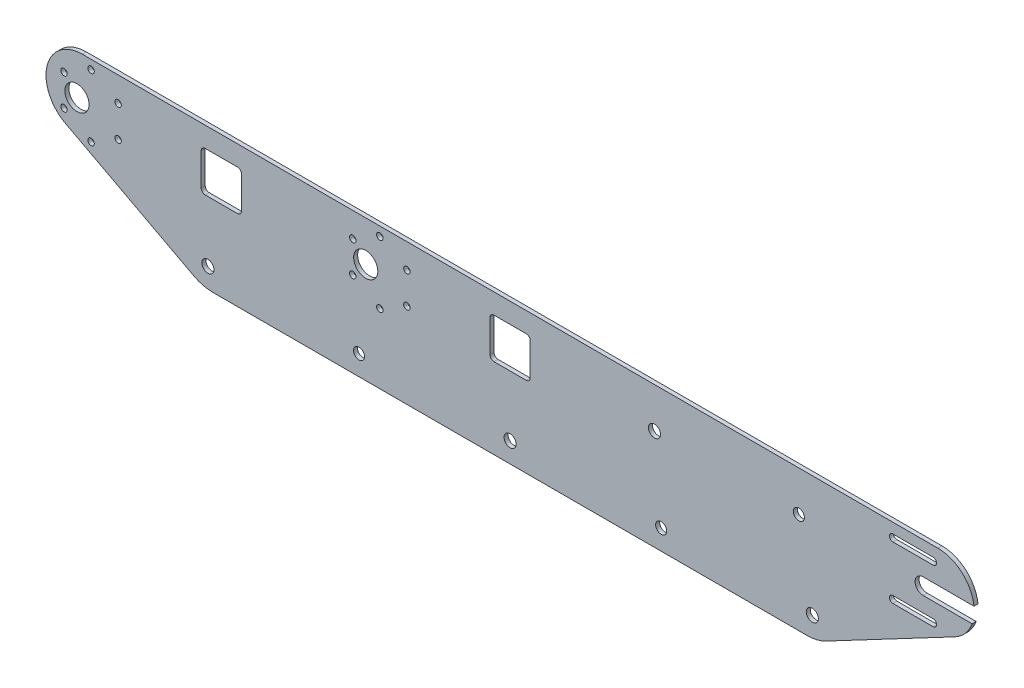
SolidWorks part; units mm, degrees
ref_plane "Plan de face" through (0, 0, 0) normal (0, 0, 1) x (1, 0, 0)
ref_plane "Plan de dessus" through (0, 0, 0) normal (0, 1, 0) x (1, 0, 0)
ref_plane "Plan de droite" through (0, 0, 0) normal (1, 0, 0) x (0, 0, -1)
sketch "Esquisse1" plane through (0, 0, 0) normal (0, 0, 1) x (1, 0, 0)
  line L0 (0, 0) -> (0, 122.747) construction
  line L1 (-215, -20) -> (215, -20) construction
  line L2 (-215, -20) -> (-215, 20) construction
  line L3 (-215, 20) -> (215, 20) construction
  line L4 (215, -20) -> (215, 20) construction
  line L5 (-215, -20) -> (215, 20) construction
  line L6 (-215, 20) -> (215, -20) construction
  line L7 (-1220, 0) -> (-150, 0) construction
  line L8 (-284.959, 40) -> (-247.3, 40)
  line L9 (248.3333, 40) -> (284.959, 40)
  line L10 (150, 0) -> (150, -20) construction
  line L11 (150, -20) -> (-150, -20) construction
  line L12 (-150, 0) -> (-150, -20) construction
  line L13 (150, 0) -> (-150, -20) construction
  line L14 (150, -20) -> (-150, 0) construction
  line L15 (-284.959, 40) -> (-247.3, 20.1016)
  line L16 (-152.4795, -30) -> (152.4795, -30)
  line L17 (284.959, 40) -> (248.3333, 20.6476)
  line L18 (-215, 20) -> (-71.6667, 20) construction
  line L19 (-71.6667, 20) -> (71.6667, 20) construction
  line L20 (71.6667, 20) -> (215, 20) construction
  line L21 (150, 0) -> (193.5165, 0) construction
  line L27 (-247.3, 20.1016) -> (-152.4795, -30)
  line L28 (248.3333, 20.6476) -> (152.4795, -30)
  line L29 (-247.3, 40) -> (248.3333, 40)
  circle A0 centre (-215, 20) radius 6
  circle A1 centre (-150, -20) radius 3
  circle A2 centre (150, -20) radius 3
  circle A3 centre (215, 20) radius 3
  circle A4 centre (0, -20) radius 3
  circle A5 centre (-71.6667, 20) radius 6
  circle A6 centre (71.6667, 20) radius 3
  point P0 (0, 0)
  point P8 (0, -10)
  point P21 (0, -30)
  dimension "D8" = 6
  dimension "D11" = 12
  dimension "D1" = 430
  dimension "D2" = 40
  dimension "D3" = 300
  dimension "D4" = 20
  dimension "D5" = 15
  dimension "D6" = 10
  dimension "D7" = 10
extrude "Boss.-Extru.1" add sketch "Esquisse1" along normal blind 2
fillet "Congé1" radius 18 2 edges at (-284.959, 40, 1) (284.959, 40, 1)
fillet "Congé2" radius 20 2 edges at (-152.4795, -30, 1) (152.4795, -30, 1)
hole_wizard "Dégagement M32" positions "Esquisse6" profile "Esquisse5" hole size "M3" standard "Ansi Metric" end condition through all
sketch "Esquisse6" plane through (0, 0, 0) normal (0, 0, -1) x (-1, 0, 0)
  line L0 (-200, 33.2288) -> (-200, 6.7712)
  circle A0 centre (-215, 20) radius 20
  circle A1 centre (-215, 20) radius 7.5
  point P0 (-200, 33.2288)
  point P2 (-200, 6.7712)
  dimension "D1" = 40
  dimension "D2" = 15
  dimension "D3" = 15
sketch "Esquisse5" plane through (200, 33.2288, 0) normal (1, 0, 0) x (0, 1, 0)
  line L0 (0, 0) -> (0, 2)
  line L1 (0, 2) -> (1.7, 2)
  line L2 (1.7, 2) -> (1.7, 0)
  line L5 (1.7, 0) -> (0, 0)
  line L11 (0, -6.35) -> (0, 107.95) construction
  dimension "Diamètre du perçage jusqu'au prochain" = 3.4
  dimension "Profondeur du perçage jusqu'au prochain" = 2
sketch "Esquisse4" plane through (0, 0, 0) normal (0, 0, -1) x (-1, 0, 0)
  line L0 (-215, 24) -> (-246.6987, 24)
  line L1 (-215, 24) -> (-205, 24)
  line L2 (-215, 16) -> (-239.4934, 16)
  line L3 (-215, 16) -> (-205, 16)
  line L4 (-215, 24) -> (-215, 16)
  line L8 (-147.5205, -30) -> (147.5205, -30)
  line L9 (156.8641, -27.6833) -> (220.7728, 6.0851)
  line L10 (156.8641, -27.6833) -> (220.7728, 6.0851)
  line L11 (212.3636, 40) -> (-212.3636, 40)
  line L12 (212.3636, 40) -> (-212.3636, 40)
  line L13 (-220.7728, 6.0851) -> (-156.8641, -27.6833)
  line L14 (-220.7728, 6.0851) -> (-156.8641, -27.6833)
  line L16 (-147.5205, -30) -> (147.5205, -30)
  arc A2 (-205, 24) -> (-205, 16) centre (-205, 20) cw
  circle A3 centre (-215, 20) radius 3 construction
  arc A6 (147.5205, -30) -> (156.8641, -27.6833) centre (147.5205, -10) ccw
  arc A7 (147.5205, -30) -> (156.8641, -27.6833) centre (147.5205, -10) ccw
  arc A8 (-156.8641, -27.6833) -> (-147.5205, -30) centre (-147.5205, -10) ccw
  arc A9 (-156.8641, -27.6833) -> (-147.5205, -30) centre (-147.5205, -10) ccw
  arc A12 (220.7728, 6.0851) -> (212.3636, 40) centre (212.3636, 22) ccw
  arc A13 (220.7728, 6.0851) -> (212.3636, 40) centre (212.3636, 22) ccw
  arc A14 (-212.3636, 40) -> (-220.7728, 6.0851) centre (-212.3636, 22) ccw
  arc A15 (-212.3636, 40) -> (-220.7728, 6.0851) centre (-212.3636, 22) ccw
  point P12 (-215, 20)
  circle M25 centre (-215, 20) radius 3
  arc M41 (-212.3636, 40) -> (-220.7728, 6.0851) centre (-212.3636, 22) ccw
  dimension "D2" = 10
  dimension "D3" = 8
  dimension "D1" = 0
extrude "Enlèv. mat.-Extru.1" cut sketch "Esquisse4" against normal through all contours A2 L1 L3 M25 | L2 L0 M25 M41
sketch "Esquisse7" plane through (0, 0, 0) normal (0, 0, -1) x (-1, 0, 0)
  line L0 (-200, 34.9288) -> (-210, 34.9288)
  line L1 (-200, 8.4712) -> (-210, 8.4712)
  line L2 (-210, 31.5288) -> (-200, 31.5288)
  line L3 (-200, 31.5288) -> (-190, 31.5288)
  line L4 (-210, 5.0712) -> (-200, 5.0712)
  line L5 (-190, 34.9288) -> (-200, 34.9288)
  line L6 (-200, 31.5288) -> (-200, 34.9288)
  line L7 (-200, 5.0712) -> (-190, 5.0712)
  line L8 (-190, 8.4712) -> (-200, 8.4712)
  line L9 (-200, 5.0712) -> (-200, 8.4712)
  circle A0 centre (-200, 33.2288) radius 1.7 construction
  arc A1 (-190, 34.9288) -> (-190, 31.5288) centre (-190, 33.2288) cw
  arc A2 (-210, 34.9288) -> (-210, 31.5288) centre (-210, 33.2288) ccw
  arc A3 (-190, 8.4712) -> (-190, 5.0712) centre (-190, 6.7712) cw
  arc A4 (-210, 8.4712) -> (-210, 5.0712) centre (-210, 6.7712) ccw
  circle A5 centre (-200, 6.7712) radius 1.7 construction
  point P11 (-200, 33.2288)
  point P19 (-200, 6.7712)
  circle M8 centre (-200, 33.2288) radius 1.7
  circle M9 centre (-200, 6.7712) radius 1.7
  dimension "D1" = 10
extrude "Enlèv. mat.-Extru.2" cut sketch "Esquisse7" against normal through all contours L1 A4 L4 M9 | A3 L8 L7 M9 | A1 L5 L3 M8 | L0 A2 L2 M8
sketch "Esquisse8" plane through (0, 0, 0) normal (0, 0, -1) x (-1, 0, 0)
  line L0 (199.334, 20) -> (153.1405, 20) construction
  line L1 (51.2433, 27.75) -> (51.2433, 12.25) construction
  line L2 (194.5766, 27.75) -> (194.5766, 12.25) construction
  line L3 (194.5766, 12.25) -> (208, 4.5) construction
  line L4 (208, 4.5) -> (221.4234, 12.25) construction
  line L5 (221.4234, 12.25) -> (221.4234, 27.75) construction
  line L6 (221.4234, 27.75) -> (208, 35.5) construction
  line L7 (208, 35.5) -> (194.5766, 27.75) construction
  line L8 (51.2433, 12.25) -> (64.6667, 4.5) construction
  line L9 (64.6667, 4.5) -> (78.0901, 12.25) construction
  line L10 (78.0901, 12.25) -> (78.0901, 27.75) construction
  line L11 (-220.7728, 6.0851) -> (-156.8641, -27.6833)
  line L12 (-220.7728, 6.0851) -> (-156.8641, -27.6833)
  line L13 (-147.5205, -30) -> (147.5205, -30)
  line L14 (156.8641, -27.6833) -> (220.7728, 6.0851)
  line L15 (156.8641, -27.6833) -> (220.7728, 6.0851)
  line L16 (212.3636, 40) -> (-212.3636, 40)
  line L17 (212.3636, 40) -> (-212.3636, 40)
  line L23 (-147.5205, -30) -> (147.5205, -30)
  line L25 (-205, 16) -> (-229.3341, 16)
  line L26 (-205, 16) -> (-229.3341, 16)
  line L27 (-230.2521, 24) -> (-205, 24)
  line L28 (-230.2521, 24) -> (-205, 24)
  line L31 (78.0901, 27.75) -> (64.6667, 35.5) construction
  line L32 (64.6667, 35.5) -> (51.2433, 27.75) construction
  circle A0 centre (71.6667, 20) radius 6 construction
  circle A2 centre (215, 20) radius 6 construction
  circle A3 centre (215, 20) radius 6 construction
  circle A4 centre (208, 20) radius 15.5 construction
  circle A5 centre (208, 20) radius 13.4234 construction
  circle A6 centre (208, 35.5) radius 1.6
  circle A7 centre (194.5766, 27.75) radius 1.6
  circle A8 centre (194.5766, 12.25) radius 1.6
  circle A9 centre (208, 4.5) radius 1.6
  circle A10 centre (221.4234, 12.25) radius 1.6
  arc A12 (-156.8641, -27.6833) -> (-147.5205, -30) centre (-147.5205, -10) ccw
  arc A13 (-156.8641, -27.6833) -> (-147.5205, -30) centre (-147.5205, -10) ccw
  arc A14 (147.5205, -30) -> (156.8641, -27.6833) centre (147.5205, -10) ccw
  arc A15 (147.5205, -30) -> (156.8641, -27.6833) centre (147.5205, -10) ccw
  arc A20 (-229.3341, 16) -> (-220.7728, 6.0851) centre (-212.3636, 22) ccw
  arc A21 (-229.3341, 16) -> (-220.7728, 6.0851) centre (-212.3636, 22) ccw
  arc A22 (220.7728, 6.0851) -> (212.3636, 40) centre (212.3636, 22) ccw
  arc A23 (220.7728, 6.0851) -> (212.3636, 40) centre (212.3636, 22) ccw
  arc A24 (-212.3636, 40) -> (-230.2521, 24) centre (-212.3636, 22) ccw
  arc A25 (-212.3636, 40) -> (-230.2521, 24) centre (-212.3636, 22) ccw
  arc A26 (-205, 16) -> (-205, 24) centre (-205, 20) ccw
  arc A27 (-205, 16) -> (-205, 24) centre (-205, 20) ccw
  circle A31 centre (221.4234, 27.75) radius 1.6
  circle A32 centre (71.6667, 20) radius 6 construction
  circle A33 centre (64.6667, 20) radius 15.5 construction
  circle A34 centre (64.6667, 20) radius 13.4234 construction
  circle A35 centre (64.6667, 35.5) radius 1.6
  circle A36 centre (51.2433, 27.75) radius 1.6
  circle A37 centre (51.2433, 12.25) radius 1.6
  circle A38 centre (64.6667, 4.5) radius 1.6
  circle A39 centre (78.0901, 12.25) radius 1.6
  circle A41 centre (78.0901, 27.75) radius 1.6
  dimension "D2" = 31
  dimension "D4" = 3.2
  dimension "D5" = 31
  dimension "D7" = 3.2
  dimension "D3" = 7
  dimension "D6" = 7
  dimension "D1" = 0
extrude "Enlèv. mat.-Extru.3" cut sketch "Esquisse8" against normal through all contours A31 | A6 | A7 | A8 | A9 | A10 | A41 | A35 | A36 | A37 | A38 | A39
hole_wizard "Dégagement M51" positions "Esquisse10" profile "Esquisse9" hole size "M5" standard "Ansi Metric" end condition through all
sketch "Esquisse10" plane through (0, 0, 0) normal (0, 0, -1) x (-1, 0, 0)
  line L0 (215, 20) -> (143.3333, 20) construction
  line L2 (143.3333, 20) -> (-208.7016, 20) construction
  line L3 (215, 20) -> (143.3333, 20)
  line L5 (143.3333, 20) -> (71.6667, 20)
  line L6 (71.6667, 20) -> (0, 20)
  line L7 (0, 20) -> (-71.6667, 20)
  line L8 (-71.6667, 20) -> (-143.3333, 20)
  circle A1 centre (215, 20) radius 6
  circle A2 centre (215, 20) radius 6 construction
  circle A3 centre (-71.6667, 20) radius 3 construction
  point P0 (143.3333, 20)
  point P2 (0, 20)
  point P4 (-143.3333, 20)
sketch "Esquisse9" plane through (-143.3333, 20, 0) normal (1, 0, 0) x (0, 1, 0)
  line L0 (0, 0) -> (0, 2)
  line L1 (0, 2) -> (2.75, 2)
  line L2 (2.75, 2) -> (2.75, 0)
  line L5 (2.75, 0) -> (0, 0)
  line L11 (0, -6.35) -> (0, 107.95) construction
  dimension "Diamètre du perçage jusqu'au prochain" = 5.5
  dimension "Profondeur du perçage jusqu'au prochain" = 2
hole_wizard "Dégagement M52" positions "Esquisse12" profile "Esquisse11" hole size "M5" standard "Ansi Metric" end condition through all
sketch "Esquisse12" plane through (0, 0, 2) normal (0, 0, 1) x (1, 0, 0)
  line L0 (-150, -20) -> (0, -20)
  line L1 (0, -20) -> (150, -20)
  circle A0 centre (-150, -20) radius 3
  circle A1 centre (0, -20) radius 3
  circle A2 centre (150, -20) radius 3
  point P17 (-75, -20)
  point P20 (75, -20)
sketch "Esquisse11" plane through (-75, -20, 2) normal (1, 0, 0) x (0, -1, 0)
  line L0 (0, 0) -> (0, 2)
  line L1 (0, 2) -> (2.75, 2)
  line L2 (2.75, 2) -> (2.75, 0)
  line L5 (2.75, 0) -> (0, 0)
  line L11 (0, -6.35) -> (0, 107.95) construction
  dimension "Diamètre du perçage jusqu'au prochain" = 5.5
  dimension "Profondeur du perçage jusqu'au prochain" = 2
sketch "Esquisse13" plane through (0, 0, 2) normal (0, 0, 1) x (1, 0, 0)
  line L1 (-153.3333, 30) -> (-133.3333, 30)
  line L2 (-153.3333, 30) -> (-153.3333, 10)
  line L3 (-153.3333, 10) -> (-133.3333, 10)
  line L4 (-133.3333, 30) -> (-133.3333, 10)
  line L5 (-153.3333, 30) -> (-133.3333, 10) construction
  line L6 (-153.3333, 10) -> (-133.3333, 30) construction
  line L7 (-10, 30) -> (10, 30)
  line L8 (-10, 30) -> (-10, 10)
  line L9 (-10, 10) -> (10, 10)
  line L10 (10, 30) -> (10, 10)
  line L11 (-10, 30) -> (10, 10) construction
  line L12 (-10, 10) -> (10, 30) construction
  point P0 (-143.3333, 20)
  point P6 (0, 20)
  dimension "D1" = 20
extrude "Enlèv. mat.-Extru.4" cut sketch "Esquisse13" against normal through all
fillet "Congé3" radius 2 8 edges at (10, 30, 1) (-10, 30, 1) (-10, 10, 1) (10, 10, 1) (-133.3333, 10, 1) (-153.3333, 10, 1) (-133.3333, 30, 1) (-153.3333, 30, 1)
